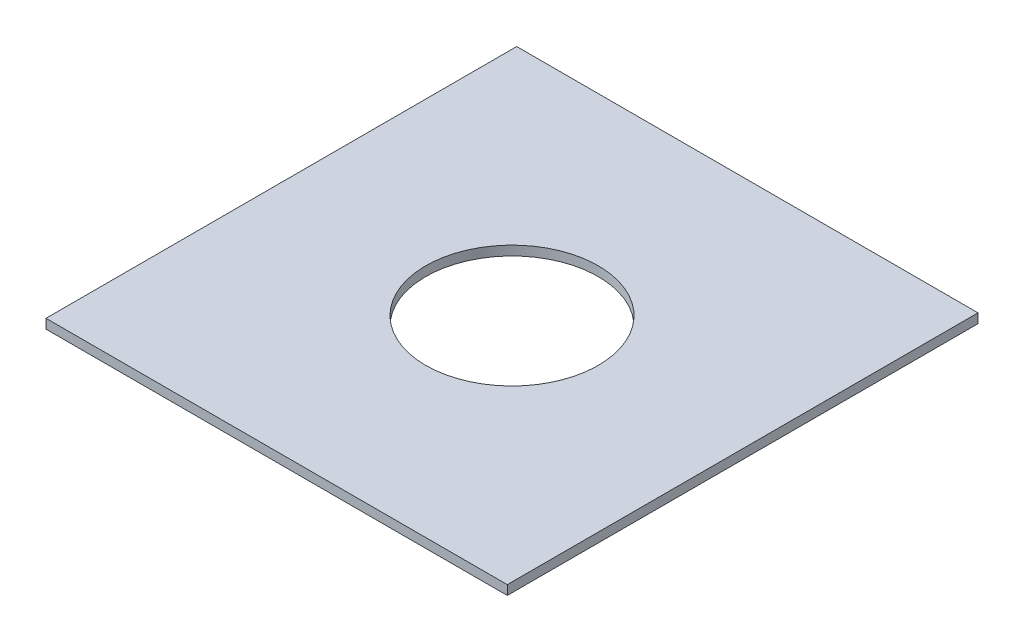
SolidWorks part; units mm, degrees
material "CA"
ref_plane "Front Plane" through (0, 0, 0) normal (0, 0, 1) x (1, 0, 0)
ref_plane "Top Plane" through (0, 0, 0) normal (0, 1, 0) x (1, 0, 0)
ref_plane "Right Plane" through (0, 0, 0) normal (1, 0, 0) x (0, 0, -1)
sketch "Sketch1" plane through (0, 0, 0) normal (0, 1, 0) x (1, 0, 0)
  line L1 (-147, 150) -> (147, 150)
  line L2 (-147, 150) -> (-147, -150)
  line L3 (-147, -150) -> (147, -150)
  line L4 (147, 150) -> (147, -150)
  circle A0 centre (0, 0) radius 55
  point P4 (0, 150)
  point P5 (-147, 0)
  dimension "D3" = 110
  dimension "D1" = 294
  dimension "D2" = 300
extrude "Boss-Extrude1" add sketch "Sketch1" along normal blind 6
